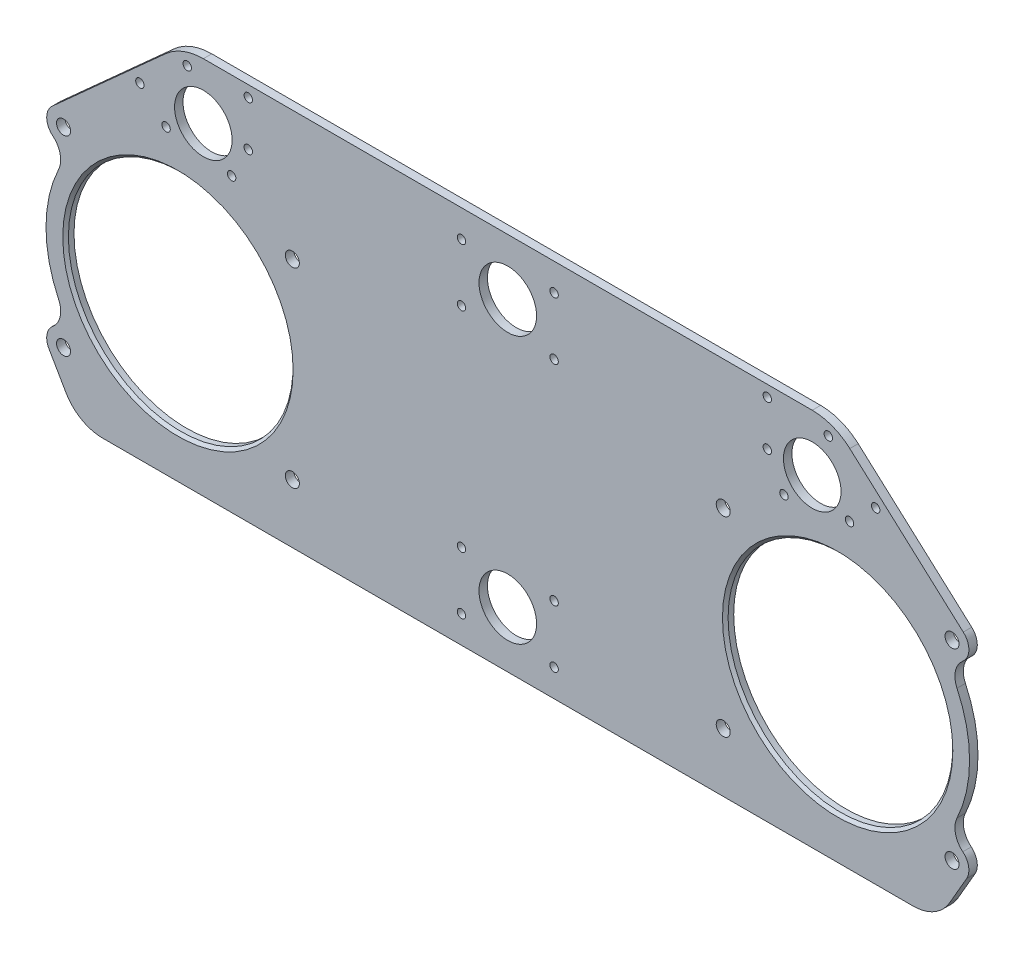
SolidWorks part; units mm, degrees
ref_plane "前视基准面" through (0, 0, 0) normal (0, 0, 1) x (1, 0, 0)
ref_plane "上视基准面" through (0, 0, 0) normal (0, 1, 0) x (1, 0, 0)
ref_plane "右视基准面" through (0, 0, 0) normal (1, 0, 0) x (0, 0, -1)
sketch "草图1" plane through (0, 0, 0) normal (0, 0, 1) x (1, 0, 0)
  line L0 (44.7648, 38.4589) -> (4.334, 74.8629)
  line L1 (-9.0486, 80) -> (-225.9514, 80)
  line L2 (0, 0) -> (-235, 0) construction
  line L3 (389.2867, 0) -> (484.3577, 0) construction
  line L4 (-117.5, 0) -> (-117.5, 88.0044) construction
  line L5 (45.9462, -37) -> (39.884, -47.5)
  line L6 (26.8936, -55) -> (-261.8936, -55)
  line L7 (-280.9462, -37) -> (-274.884, -47.5)
  line L8 (-279.7648, 38.4589) -> (-239.334, 74.8629)
  arc A0 (-262.3166, -38.2466) -> (-207.6834, -38.2466) centre (-235, 0) ccw construction
  arc A1 (-262.3166, -38.2466) -> (-271.9061, -38.607) centre (-266.8781, -44.6332) ccw construction
  arc A2 (-279.5939, -29.393) -> (-271.9061, -38.607) centre (-275.75, -34) ccw construction
  arc A3 (-279.5939, -29.393) -> (-277.5214, -20.0232) centre (-284.6219, -23.3668) ccw construction
  arc A4 (-277.5214, 20.0232) -> (-277.5214, -20.0232) centre (-235, 0) ccw construction
  arc A5 (-277.5214, 20.0232) -> (-279.5939, 29.393) centre (-284.6219, 23.3668) ccw construction
  arc A6 (-271.9061, 38.607) -> (-279.5939, 29.393) centre (-275.75, 34) ccw construction
  arc A7 (-271.9061, 38.607) -> (-262.3166, 38.2466) centre (-266.8781, 44.6332) ccw construction
  arc A8 (-207.6834, 38.2466) -> (-262.3166, 38.2466) centre (-235, 0) ccw construction
  arc A9 (-207.6834, 38.2466) -> (-198.0939, 38.607) centre (-203.1219, 44.6332) ccw construction
  arc A10 (-190.4061, 29.393) -> (-198.0939, 38.607) centre (-194.25, 34) ccw construction
  arc A11 (-190.4061, 29.393) -> (-192.4786, 20.0232) centre (-185.3781, 23.3668) ccw construction
  arc A12 (-192.4786, -20.0232) -> (-192.4786, 20.0232) centre (-235, 0) ccw construction
  arc A13 (-192.4786, -20.0232) -> (-190.4061, -29.393) centre (-185.3781, -23.3668) ccw construction
  arc A14 (-198.0939, -38.607) -> (-190.4061, -29.393) centre (-194.25, -34) ccw construction
  arc A15 (-198.0939, -38.607) -> (-207.6834, -38.2466) centre (-203.1219, -44.6332) ccw construction
  arc A16 (-27.3166, -38.2466) -> (27.3166, -38.2466) centre (0, 0) ccw construction
  arc A17 (-27.3166, -38.2466) -> (-36.9061, -38.607) centre (-31.8781, -44.6332) ccw construction
  arc A18 (-44.5939, -29.393) -> (-36.9061, -38.607) centre (-40.75, -34) ccw construction
  arc A19 (-44.5939, -29.393) -> (-42.5214, -20.0232) centre (-49.6219, -23.3668) ccw construction
  arc A20 (-42.5214, 20.0232) -> (-42.5214, -20.0232) centre (0, 0) ccw construction
  arc A21 (-42.5214, 20.0232) -> (-44.5939, 29.393) centre (-49.6219, 23.3668) ccw construction
  arc A22 (-36.9061, 38.607) -> (-44.5939, 29.393) centre (-40.75, 34) ccw construction
  arc A23 (-36.9061, 38.607) -> (-27.3166, 38.2466) centre (-31.8781, 44.6332) ccw construction
  arc A24 (27.3166, 38.2466) -> (-27.3166, 38.2466) centre (0, 0) ccw construction
  arc A25 (27.3166, 38.2466) -> (36.9061, 38.607) centre (31.8781, 44.6332) ccw construction
  arc A26 (44.5939, 29.393) -> (36.9061, 38.607) centre (40.75, 34) ccw construction
  arc A27 (44.5939, 29.393) -> (42.5214, 20.0232) centre (49.6219, 23.3668) ccw construction
  arc A28 (42.5214, -20.0232) -> (42.5214, 20.0232) centre (0, 0) ccw construction
  arc A29 (42.5214, -20.0232) -> (44.5939, -29.393) centre (49.6219, -23.3668) ccw construction
  arc A30 (36.9061, -38.607) -> (44.5939, -29.393) centre (40.75, -34) ccw construction
  arc A31 (36.9061, -38.607) -> (27.3166, -38.2466) centre (31.8781, -44.6332) ccw construction
  arc A32 (-262.3166, -38.2466) -> (-207.6834, -38.2466) centre (-235, 0) ccw construction
  arc A33 (-262.3166, -38.2466) -> (-271.9061, -38.607) centre (-266.8781, -44.6332) ccw construction
  arc A34 (-279.5939, -29.393) -> (-271.9061, -38.607) centre (-275.75, -34) ccw construction
  arc A35 (-279.5939, -29.393) -> (-277.5214, -20.0232) centre (-284.6219, -23.3668) ccw construction
  arc A36 (-277.5214, 20.0232) -> (-277.5214, -20.0232) centre (-235, 0) ccw construction
  arc A37 (-277.5214, 20.0232) -> (-279.5939, 29.393) centre (-284.6219, 23.3668) ccw construction
  arc A38 (-271.9061, 38.607) -> (-279.5939, 29.393) centre (-275.75, 34) ccw construction
  arc A39 (-271.9061, 38.607) -> (-262.3166, 38.2466) centre (-266.8781, 44.6332) ccw construction
  arc A40 (-207.6834, 38.2466) -> (-262.3166, 38.2466) centre (-235, 0) ccw construction
  arc A41 (-207.6834, 38.2466) -> (-198.0939, 38.607) centre (-203.1219, 44.6332) ccw construction
  arc A42 (-190.4061, 29.393) -> (-198.0939, 38.607) centre (-194.25, 34) ccw construction
  arc A43 (-190.4061, 29.393) -> (-192.4786, 20.0232) centre (-185.3781, 23.3668) ccw construction
  arc A44 (-192.4786, -20.0232) -> (-192.4786, 20.0232) centre (-235, 0) ccw construction
  arc A45 (-192.4786, -20.0232) -> (-190.4061, -29.393) centre (-185.3781, -23.3668) ccw construction
  arc A46 (-198.0939, -38.607) -> (-190.4061, -29.393) centre (-194.25, -34) ccw construction
  arc A47 (-198.0939, -38.607) -> (-207.6834, -38.2466) centre (-203.1219, -44.6332) ccw construction
  arc A48 (-27.3166, -38.2466) -> (27.3166, -38.2466) centre (0, 0) ccw construction
  arc A49 (-27.3166, -38.2466) -> (-36.9061, -38.607) centre (-31.8781, -44.6332) ccw construction
  arc A50 (-44.5939, -29.393) -> (-36.9061, -38.607) centre (-40.75, -34) ccw construction
  arc A51 (-44.5939, -29.393) -> (-42.5214, -20.0232) centre (-49.6219, -23.3668) ccw construction
  arc A52 (-42.5214, 20.0232) -> (-42.5214, -20.0232) centre (0, 0) ccw construction
  arc A53 (-42.5214, 20.0232) -> (-44.5939, 29.393) centre (-49.6219, 23.3668) ccw construction
  arc A54 (-36.9061, 38.607) -> (-44.5939, 29.393) centre (-40.75, 34) ccw construction
  arc A55 (-36.9061, 38.607) -> (-27.3166, 38.2466) centre (-31.8781, 44.6332) ccw construction
  arc A56 (27.3166, 38.2466) -> (-27.3166, 38.2466) centre (0, 0) ccw construction
  arc A57 (27.3166, 38.2466) -> (36.9061, 38.607) centre (31.8781, 44.6332) ccw construction
  arc A58 (44.5939, 29.393) -> (36.9061, 38.607) centre (40.75, 34) ccw construction
  arc A59 (44.5939, 29.393) -> (42.5214, 20.0232) centre (49.6219, 23.3668) ccw
  arc A60 (42.5214, -20.0232) -> (42.5214, 20.0232) centre (0, 0) ccw
  arc A61 (42.5214, -20.0232) -> (44.5939, -29.393) centre (49.6219, -23.3668) ccw
  arc A62 (36.9061, -38.607) -> (44.5939, -29.393) centre (40.75, -34) ccw construction
  arc A63 (36.9061, -38.607) -> (27.3166, -38.2466) centre (31.8781, -44.6332) ccw construction
  arc A65 (44.7648, 38.4589) -> (44.5939, 29.393) centre (40.75, 34) cw
  arc A66 (44.5939, -29.393) -> (45.9462, -37) centre (40.75, -34) cw
  arc A67 (39.884, -47.5) -> (26.8936, -55) centre (26.8936, -40) cw
  arc A68 (4.334, 74.8629) -> (-9.0486, 80) centre (-9.0486, 60) ccw
  arc A69 (-271.9061, -38.607) -> (-262.3166, -38.2466) centre (-266.8781, -44.6332) cw construction
  arc A70 (-271.9061, -38.607) -> (-279.5939, -29.393) centre (-275.75, -34) cw construction
  arc A71 (-279.5939, 29.393) -> (-271.9061, 38.607) centre (-275.75, 34) cw construction
  arc A72 (-262.3166, 38.2466) -> (-271.9061, 38.607) centre (-266.8781, 44.6332) cw construction
  arc A73 (-262.3166, 38.2466) -> (-207.6834, 38.2466) centre (-235, 0) cw construction
  arc A74 (-198.0939, 38.607) -> (-207.6834, 38.2466) centre (-203.1219, 44.6332) cw construction
  arc A75 (-198.0939, 38.607) -> (-190.4061, 29.393) centre (-194.25, 34) cw construction
  arc A76 (-192.4786, 20.0232) -> (-190.4061, 29.393) centre (-185.3781, 23.3668) cw construction
  arc A77 (-192.4786, 20.0232) -> (-192.4786, -20.0232) centre (-235, 0) cw construction
  arc A78 (-190.4061, -29.393) -> (-192.4786, -20.0232) centre (-185.3781, -23.3668) cw construction
  arc A79 (-190.4061, -29.393) -> (-198.0939, -38.607) centre (-194.25, -34) cw construction
  arc A80 (-207.6834, -38.2466) -> (-198.0939, -38.607) centre (-203.1219, -44.6332) cw construction
  arc A81 (-207.6834, -38.2466) -> (-262.3166, -38.2466) centre (-235, 0) cw construction
  arc A82 (-239.334, 74.8629) -> (-225.9514, 80) centre (-225.9514, 60) cw
  arc A83 (-274.884, -47.5) -> (-261.8936, -55) centre (-261.8936, -40) ccw
  arc A84 (-279.5939, -29.393) -> (-280.9462, -37) centre (-275.75, -34) ccw
  arc A85 (-279.7648, 38.4589) -> (-279.5939, 29.393) centre (-275.75, 34) ccw
  arc A86 (-277.5214, -20.0232) -> (-279.5939, -29.393) centre (-284.6219, -23.3668) cw
  arc A87 (-277.5214, -20.0232) -> (-277.5214, 20.0232) centre (-235, 0) cw
  arc A88 (-279.5939, 29.393) -> (-277.5214, 20.0232) centre (-284.6219, 23.3668) cw
  circle A89 centre (0, 0) radius 40.0281
  circle A90 centre (-235, 0) radius 40.0281
  arc A91 (29.3152, -27.2557) -> (3.7343, 39.8535) centre (0, 0) ccw construction
  point P16 (-117.5, 0)
  point P32 (-117.5, 80)
  point P80 (-117.5, -55)
  dimension "D5" = 15
  dimension "D6" = 20
  dimension "D1" = 138
  dimension "D2" = 80
  dimension "D3" = 120
  dimension "D4" = 55
extrude "凸台-拉伸1" add sketch "草图1" along normal blind 3
chamfer "倒角1" distance 1 angle 45
sketch "草图2" plane through (0, 0, 0) normal (0, 0, -1) x (-1, 0, 0)
  circle A0 centre (40.75, -34) radius 2.5 construction
  circle A1 centre (40.75, 34) radius 2.5 construction
  circle A2 centre (-40.75, 34) radius 2.5 construction
  circle A3 centre (-40.75, -34) radius 2.5 construction
  circle A4 centre (40.75, -34) radius 2.5
  circle A5 centre (40.75, 34) radius 2.5
  circle A6 centre (-40.75, 34) radius 2.5
  circle A7 centre (-40.75, -34) radius 2.5
  circle A8 centre (275.75, -34) radius 2.5 construction
  circle A9 centre (275.75, 34) radius 2.5 construction
  circle A10 centre (194.25, 34) radius 2.5 construction
  circle A11 centre (194.25, -34) radius 2.5 construction
  circle A12 centre (275.75, -34) radius 2.5
  circle A13 centre (275.75, 34) radius 2.5
  circle A14 centre (194.25, 34) radius 2.5
  circle A15 centre (194.25, -34) radius 2.5
extrude "切除-拉伸1" cut sketch "草图2" against normal through all both and the other way through all
sketch "草图3" plane through (0, 0, 3) normal (0, 0, 1) x (1, 0, 0)
  line L0 (-40.75, -34) -> (-194.25, -34) construction
  line L1 (-117.5, -34) -> (-117.5, -55) construction
  line L2 (-261.8936, -55) -> (26.8936, -55) construction
  line L4 (-9.0486, 80) -> (-225.9514, 80) construction
  circle A1 centre (-117.5, -35) radius 10.25
  circle A4 centre (-225.9514, 60) radius 10.25
  arc A5 (-225.9514, 80) -> (-239.334, 74.8629) centre (-225.9514, 60) ccw construction
  circle A6 centre (-117.5, 60) radius 10.25
  circle A7 centre (-9.0486, 60) radius 10.25
  point P5 (-117.5, -34)
  dimension "D1" = 20.5
  dimension "D3" = 20.5
  dimension "D4" = 20.5
  dimension "D2" = 20
  dimension "D5" = 20
extrude "切除-拉伸2" cut sketch "草图3" against normal through all both and the other way through all
sketch "草图4" plane through (0, 0, 0) normal (0, 0, -1) x (-1, 0, 0)
  circle A1 centre (134, -24.75) radius 1.5
  circle A2 centre (134, -24.75) radius 1.5
  circle A3 centre (134, -45.25) radius 1.5
  circle A4 centre (134, -45.25) radius 1.5
  circle A5 centre (101, -45.25) radius 1.5
  circle A6 centre (101, -45.25) radius 1.5
  circle A7 centre (101, -24.75) radius 1.5
  circle A8 centre (101, -24.75) radius 1.5
  dimension "D1" = 0
  dimension "D2" = 0
  dimension "D3" = 0
  dimension "D4" = 0
extrude "切除-拉伸3" cut sketch "草图4" against normal through all both and the other way through all
sketch "草图5" plane through (0, 0, 0) normal (0, 0, -1) x (-1, 0, 0)
  circle A1 centre (19.1282, 48.8913) radius 1.5
  circle A2 centre (19.1282, 48.8913) radius 1.5
  circle A3 centre (25.0486, 60) radius 1.5
  circle A4 centre (25.0486, 60) radius 1.5
  circle A5 centre (25.0486, 76) radius 1.5
  circle A6 centre (25.0486, 76) radius 1.5
  circle A7 centre (3.3147, 74.9373) radius 1.5
  circle A8 centre (3.3147, 74.9373) radius 1.5
  circle A9 centre (-13.5478, 61.1842) radius 1.5
  circle A10 centre (-13.5478, 61.1842) radius 1.5
  circle A11 centre (-4.2292, 52.3294) radius 1.5
  circle A12 centre (-4.2292, 52.3294) radius 1.5
  circle A13 centre (209.9514, 60) radius 1.5
  circle A14 centre (209.9514, 60) radius 1.5
  circle A15 centre (215.8718, 48.8913) radius 1.5
  circle A16 centre (215.8718, 48.8913) radius 1.5
  circle A17 centre (239.2292, 52.3294) radius 1.5
  circle A18 centre (239.2292, 52.3294) radius 1.5
  circle A19 centre (248.5478, 61.1842) radius 1.5
  circle A20 centre (248.5478, 61.1842) radius 1.5
  circle A21 centre (209.9514, 76) radius 1.5
  circle A22 centre (209.9514, 76) radius 1.5
  circle A23 centre (231.6853, 74.9373) radius 1.5
  circle A24 centre (231.6853, 74.9373) radius 1.5
  dimension "D1" = 0
  dimension "D2" = 0
  dimension "D3" = 0
  dimension "D4" = 0
  dimension "D5" = 0
  dimension "D6" = 0
  dimension "D7" = 0
  dimension "D8" = 0
  dimension "D9" = 0
  dimension "D10" = 0
  dimension "D11" = 0
  dimension "D12" = 0
extrude "切除-拉伸4" cut sketch "草图5" against normal through all both and the other way through all
sketch "草图6" plane through (0, 0, 0) normal (0, 0, -1) x (-1, 0, 0)
  circle A1 centre (134, 70.25) radius 1.5
  circle A2 centre (134, 70.25) radius 1.5
  circle A3 centre (134, 49.75) radius 1.5
  circle A4 centre (134, 49.75) radius 1.5
  circle A5 centre (101, 70.25) radius 1.5
  circle A6 centre (101, 70.25) radius 1.5
  circle A7 centre (101, 49.75) radius 1.5
  circle A8 centre (101, 49.75) radius 1.5
  dimension "D1" = 0
  dimension "D2" = 0
  dimension "D3" = 0
  dimension "D4" = 0
extrude "切除-拉伸5" cut sketch "草图6" against normal through all both and the other way through all
